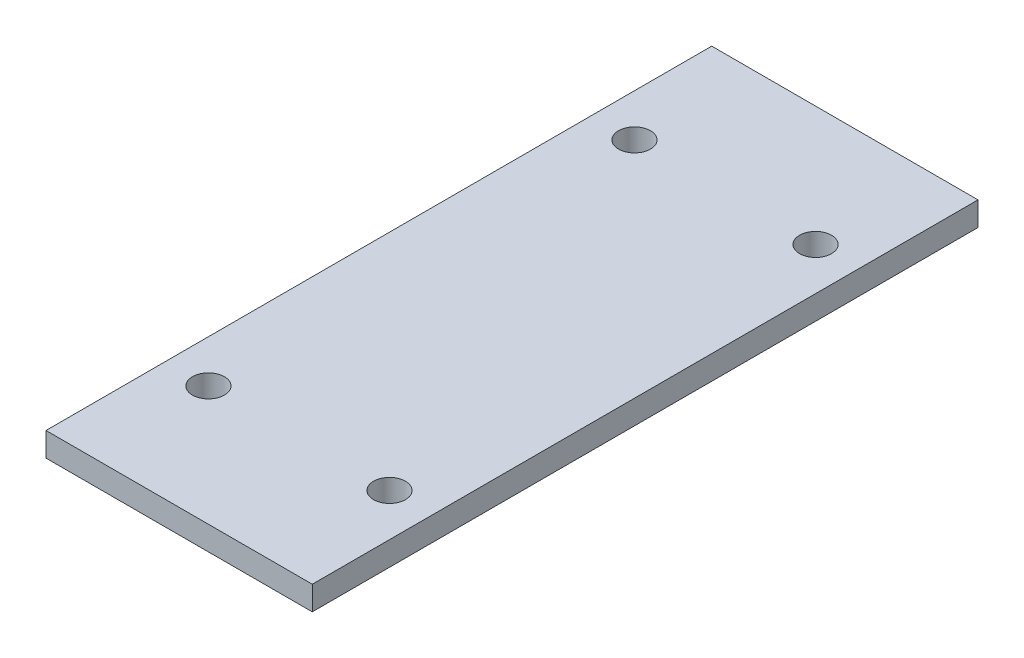
SolidWorks part; units mm, degrees
ref_plane "Front Plane" through (0, 0, 0) normal (0, 0, 1) x (1, 0, 0)
ref_plane "Top Plane" through (0, 0, 0) normal (0, 1, 0) x (1, 0, 0)
ref_plane "Right Plane" through (0, 0, 0) normal (1, 0, 0) x (0, 0, -1)
sketch "Sketch1" plane through (0, 0, 0) normal (0, 0, 1) x (1, 0, 0)
  line L1 (0, 0) -> (100, 0)
  line L2 (0, 0) -> (0, -9)
  line L3 (0, -9) -> (100, -9)
  line L4 (100, 0) -> (100, -9)
  dimension "D1" = 9
  dimension "D2" = 100
extrude "Boss-Extrude1" add sketch "Sketch1" along normal blind 250 contours L3 L4 L1 L2
sketch "Sketch2" plane through (0, 0, 0) normal (0, 1, 0) x (1, 0, 0)
  line L0 (100, -250) -> (100, 0) construction
  line L1 (0, -250) -> (0, 0) construction
  line L2 (0, 0) -> (100, 0) construction
  circle A0 centre (16, -45) radius 6
  circle A1 centre (84, -45) radius 6
  circle A2 centre (16, -205) radius 6
  circle A3 centre (84, -205) radius 6
  dimension "D1" = 12
  dimension "D2" = 12
  dimension "D3" = 12
  dimension "D4" = 12
  dimension "D5" = 160
  dimension "D6" = 16
  dimension "D7" = 16
  dimension "D8" = 45
extrude "Cut-Extrude2" cut sketch "Sketch2" against normal through all
equation "\"D7@Sketch2\"=\"D6@Sketch2\""
equation "\"D4@Sketch2\"=\"D3@Sketch2\""
equation "\"D2@Sketch2\"=\"D3@Sketch2\""
equation "\"D1@Sketch2\"=\"D3@Sketch2\""
